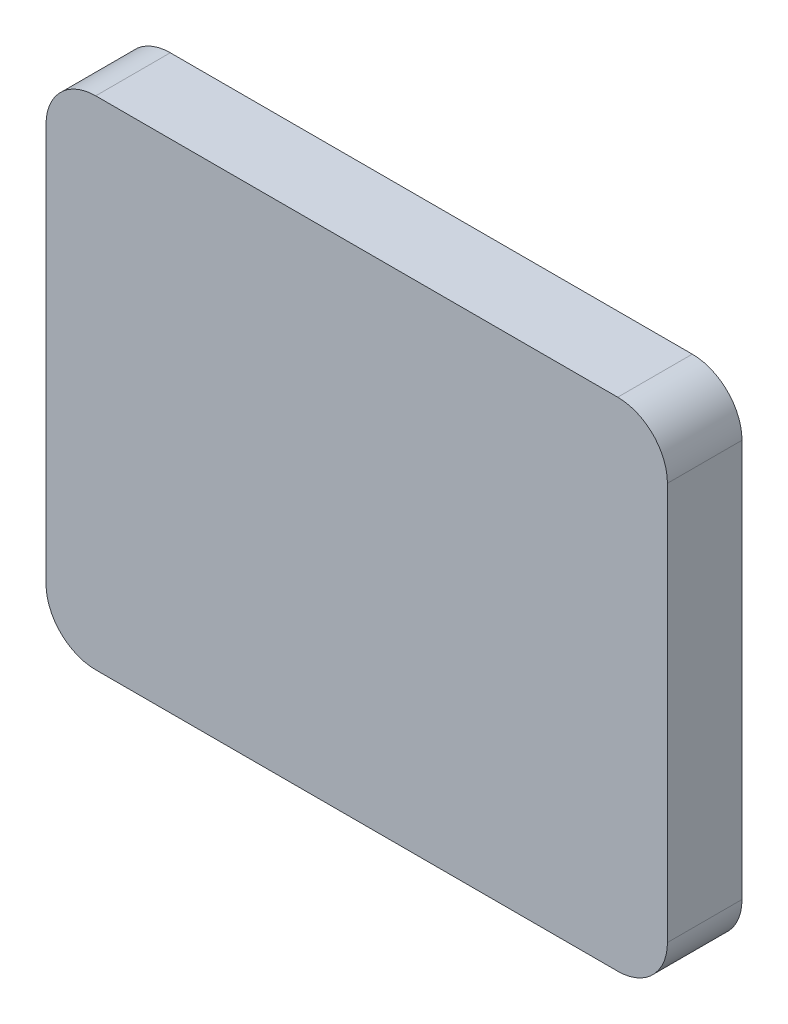
SolidWorks part; units mm, degrees
ref_plane "Plano frontal" through (0, 0, 0) normal (0, 0, 1) x (1, 0, 0)
ref_plane "Plano superior" through (0, 0, 0) normal (0, 1, 0) x (1, 0, 0)
ref_plane "Plano direito" through (0, 0, 0) normal (1, 0, 0) x (0, 0, -1)
sketch "Esboço1" plane through (0, 0, 0) normal (0, 0, 1) x (1, 0, 0)
  line L1 (12.5, -10) -> (-12.5, -10)
  line L2 (12.5, -10) -> (12.5, 10)
  line L3 (12.5, 10) -> (-12.5, 10)
  line L4 (-12.5, -10) -> (-12.5, 10)
  line L5 (12.5, -10) -> (-12.5, 10) construction
  line L6 (12.5, 10) -> (-12.5, -10) construction
  point P0 (0, 0)
  dimension "D1" = 20
  dimension "D2" = 25
extrude "Ressalto-extrusão1" add sketch "Esboço1" along normal blind 3
fillet "Filete1" radius 2 4 edges at (-12.5, 10, 1.5) (-12.5, -10, 1.5) (12.5, -10, 1.5) (12.5, 10, 1.5)
